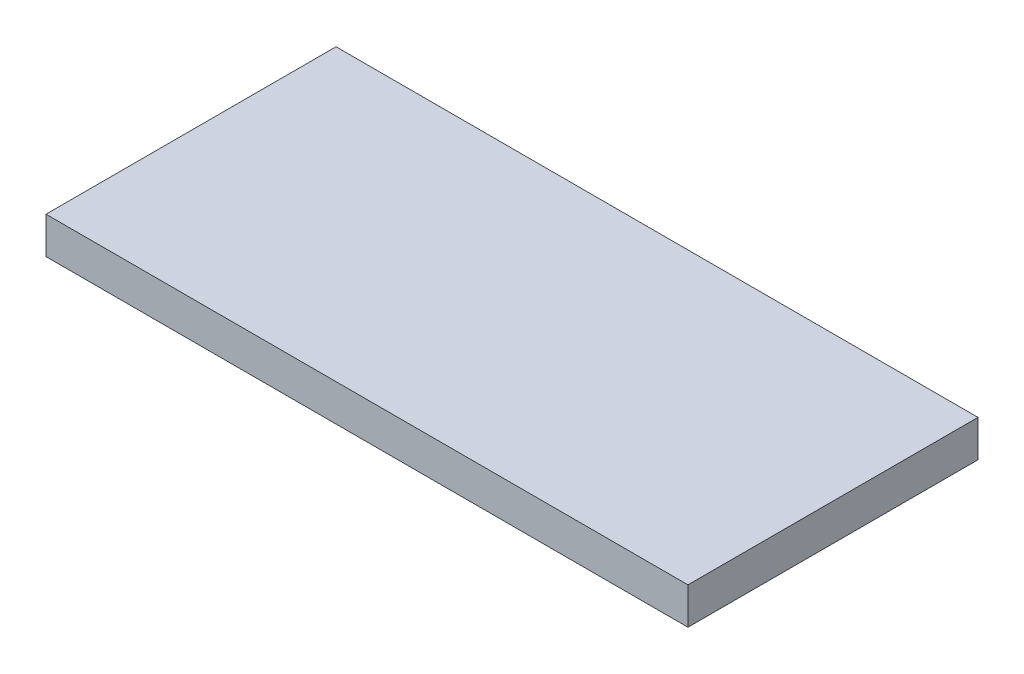
SolidWorks part; units mm, degrees
ref_plane "Alzado" through (0, 0, 0) normal (0, 0, 1) x (1, 0, 0)
ref_plane "Planta" through (0, 0, 0) normal (0, 1, 0) x (1, 0, 0)
ref_plane "Vista lateral" through (0, 0, 0) normal (1, 0, 0) x (0, 0, -1)
sketch "Croquis3" plane through (0, 0, 0) normal (0, 1, 0) x (1, 0, 0)
  line L1 (-138.5285, 77.0714) -> (193.4715, 77.0714)
  line L2 (-138.5285, 77.0714) -> (-138.5285, -72.9286)
  line L3 (-138.5285, -72.9286) -> (193.4715, -72.9286)
  line L4 (193.4715, 77.0714) -> (193.4715, -72.9286)
  dimension "D1" = 332
  dimension "D2" = 150
extrude "Saliente-Extruir1" add sketch "Croquis3" along normal blind 19
